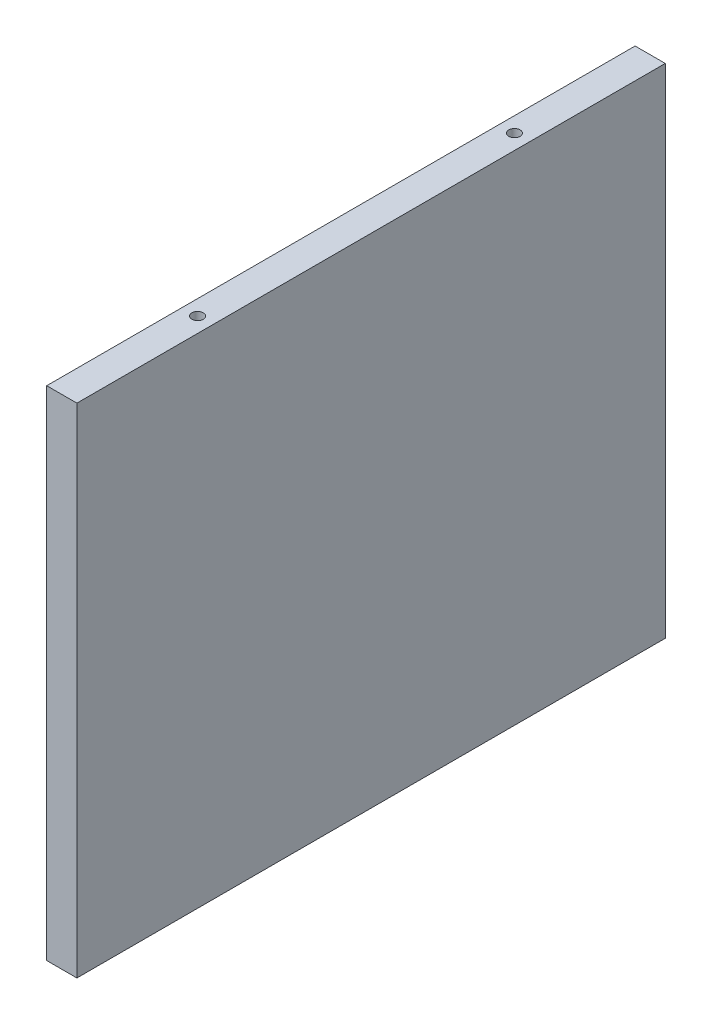
SolidWorks part; units mm, degrees
material "Pin"
ref_plane "Plan de face" through (0, 0, 0) normal (0, 0, 1) x (1, 0, 0)
ref_plane "Plan de dessus" through (0, 0, 0) normal (0, 1, 0) x (1, 0, 0)
ref_plane "Plan de droite" through (0, 0, 0) normal (1, 0, 0) x (0, 0, -1)
sketch "Esquisse1" plane through (0, 0, 0) normal (0, 1, 0) x (1, 0, 0)
  line L1 (-10, -195) -> (10, -195)
  line L2 (-10, -195) -> (-10, 195)
  line L3 (-10, 195) -> (10, 195)
  line L4 (10, -195) -> (10, 195)
  line L5 (-10, -195) -> (10, 195) construction
  line L6 (-10, 195) -> (10, -195) construction
  point P0 (0, 0)
  dimension "D1" = 390
  dimension "D2" = 20
extrude "Boss.-Extru.1" add sketch "Esquisse1" along normal blind 330
sketch "Esquisse2" plane through (0, 330, 0) normal (0, 1, 0) x (1, 0, 0)
  line L0 (0, 195) -> (0, 105) construction
  line L1 (10, 195) -> (-10, 195) construction
  line L2 (0, -195) -> (0, -105) construction
  line L3 (-10, -195) -> (10, -195) construction
  circle A0 centre (0, 105) radius 3.75
  circle A1 centre (0, -105) radius 3.75
  dimension "D1" = 7.5
  dimension "D2" = 7.5
  dimension "D3" = 90
  dimension "D4" = 90
extrude "Enlèv. mat.-Extru.1" cut sketch "Esquisse2" against normal blind 10
sketch "Esquisse3" plane through (0, 0, 0) normal (0, -1, 0) x (1, 0, 0)
  line L0 (0, 195) -> (0, 105) construction
  line L1 (-10, 195) -> (10, 195) construction
  line L2 (0, -195) -> (0, -105) construction
  line L3 (10, -195) -> (-10, -195) construction
  circle A0 centre (0, -105) radius 3.75
  circle A1 centre (0, 105) radius 3.75
  dimension "D3" = 7.5
  dimension "D4" = 7.5
  dimension "D1" = 90
  dimension "D2" = 90
extrude "Enlèv. mat.-Extru.2" cut sketch "Esquisse3" against normal blind 10
